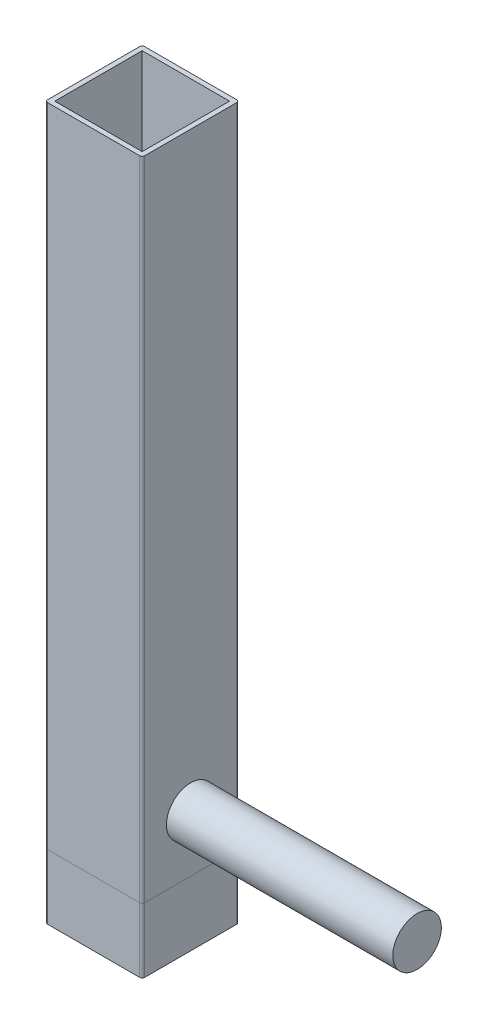
SolidWorks part; units mm, degrees
material "AISI 1035 Acero (SS)"
material "AISI 1035 Acero (SS)"
material "AISI 1035 Acero (SS)"
ref_plane "Alzado" through (0, 0, 0) normal (0, 0, 1) x (1, 0, 0)
ref_plane "Planta" through (0, 0, 0) normal (0, 1, 0) x (1, 0, 0)
ref_plane "Vista lateral" through (0, 0, 0) normal (1, 0, 0) x (0, 0, -1)
sketch "Croquis1" plane through (0, 0, 0) normal (0, 0, 1) x (1, 0, 0)
  line L0 (0, 254) -> (0, 0)
  line L1 (0, 0) -> (0, -25.4)
  dimension "D1" = 254
  dimension "D2" = 25.4
other "Ptr PTR_1.5X1.5_CALIBRE14(1)"
ref_plane "Plano1" through (0, 254, 0) normal (0, -1, 0) x (1, 0, 0)
sketch "Croquis11" plane through (0, 254, 0) normal (0, -1, 0) x (1, 0, 0)
  line L0 (-17.16, -17.16) -> (-17.16, 17.16)
  line L1 (-18.05, -19.05) -> (18.05, -19.05)
  line L2 (-19.05, -18.05) -> (-19.05, 18.05)
  line L3 (-18.05, 19.05) -> (18.05, 19.05)
  line L4 (19.05, -18.05) -> (19.05, 18.05)
  line L5 (-19.05, -19.05) -> (19.05, 19.05) construction
  line L6 (-19.05, 19.05) -> (19.05, -19.05) construction
  line L7 (-17.16, 17.16) -> (17.16, 17.16)
  line L8 (17.16, -17.16) -> (17.16, 17.16)
  line L9 (-17.16, -17.16) -> (17.16, -17.16)
  line L10 (-19.05, 19.05) -> (19.05, 19.05) construction
  line L11 (19.05, -19.05) -> (19.05, 19.05) construction
  line L12 (-19.05, -19.05) -> (19.05, -19.05) construction
  line L13 (-19.05, -19.05) -> (-19.05, 19.05) construction
  arc A0 (18.05, 19.05) -> (19.05, 18.05) centre (18.05, 18.05) cw
  arc A1 (18.05, -19.05) -> (19.05, -18.05) centre (18.05, -18.05) ccw
  arc A2 (-18.05, -19.05) -> (-19.05, -18.05) centre (-18.05, -18.05) cw
  arc A3 (-19.05, 18.05) -> (-18.05, 19.05) centre (-18.05, 18.05) cw
  point P0 (0, 0)
  point P10 (0, 0)
  dimension "D2" = 1
  dimension "D1" = 38.1
  dimension "D3" = 1.89
sketch "Croquis13" plane through (19.05, 0, 0) normal (1, 0, 0) x (0, 0, -1)
  line L0 (18.05, 0) -> (-18.05, 0) construction
  circle A0 centre (0, 22.225) radius 9.525
  dimension "D1" = 19.05
  dimension "D2" = 22.225
extrude "Saliente-Extruir1" add sketch "Croquis13" along normal blind 88.9 separate body
sketch "Croquis15" plane through (19.05, 0, 0) normal (1, 0, 0) x (0, 0, -1)
  line L9 (24.05, -25.4) -> (24.05, 101.6)
  line L11 (18.05, 0) -> (-18.05, 0) construction
  line L12 (0, 104.6) -> (0, -28.4) construction
  line L13 (-24.05, -25.4) -> (24.05, -25.4)
  line L15 (24.05, 101.6) -> (-24.05, 101.6)
  line L16 (-24.05, 101.6) -> (-24.05, -25.4)
  line L17 (-27.05, -28.4) -> (27.05, -28.4)
  line L18 (27.05, -28.4) -> (27.05, 104.6)
  line L19 (27.05, 104.6) -> (-27.05, 104.6)
  line L20 (-27.05, 104.6) -> (-27.05, -28.4)
  line L22 (-19.05, 0) -> (-19.05, 254) construction
  line L23 (24.05, -11.1836) -> (6.05, -11.1836)
  line L29 (24.05, -25.4) -> (24.05, 101.6) construction
  dimension "D1" = 3
  dimension "D3" = 101.6
  dimension "D4" = 18
  dimension "D2" = 25.4
  dimension "D5" = 5
sketch "Croquis16" plane through (0, 0, 19.05) normal (0, 0, 1) x (1, 0, 0)
  line L0 (-31.75, -25.4) -> (-31.75, 101.6)
  line L1 (-31.75, 101.6) -> (31.75, 101.6)
  line L2 (31.75, 101.6) -> (31.75, 69.85)
  line L3 (44.45, 44.45) -> (120.65, 44.45)
  line L4 (120.65, 44.45) -> (120.65, 0)
  line L5 (31.75, -25.4) -> (-31.75, -25.4)
  line L6 (18.05, 0) -> (-18.05, 0) construction
  line L7 (-19.05, 0) -> (-19.05, 254) construction
  line L8 (19.05, 0) -> (19.05, 254) construction
  line L9 (107.95, 31.75) -> (19.05, 31.75) construction
  line L10 (107.95, 12.7) -> (107.95, 31.75) construction
  line L11 (31.75, -25.4) -> (44.45, 0)
  line L12 (44.45, 0) -> (120.65, 0)
  line L13 (19.05, 12.7) -> (107.95, 12.7) construction
  line L14 (31.75, 69.85) -> (44.45, 44.45)
  dimension "D1" = 25.4
  dimension "D2" = 101.6
  dimension "D3" = 12.7
  dimension "D4" = 12.7
  dimension "D5" = 12.7
  dimension "D6" = 12.7
  dimension "D7" = 12.7
  dimension "D8" = 76.2
sketch "Croquis17" plane through (0, 0, 19.05) normal (0, 0, 1) x (1, 0, 0)
  line L0 (-19.05, 0) -> (19.05, 0)
  line L1 (19.05, 0) -> (19.05, 12.7)
  line L2 (19.05, 12.7) -> (107.95, 12.7) construction
  line L3 (19.05, 31.75) -> (19.05, 12.7) construction
  line L4 (19.05, 12.7) -> (107.95, 12.7)
  line L5 (107.95, 12.7) -> (107.95, 31.75)
  line L6 (107.95, 31.75) -> (19.05, 31.75)
  line L7 (19.05, 0) -> (19.05, 254) construction
  line L8 (107.95, 31.75) -> (19.05, 31.75) construction
  line L9 (19.05, 31.75) -> (19.05, 101.6)
  line L10 (19.05, 101.6) -> (-19.05, 101.6)
  line L11 (-19.05, 0) -> (-19.05, 254) construction
  line L12 (-19.05, 101.6) -> (-19.05, 0)
  dimension "D1" = 101.6
